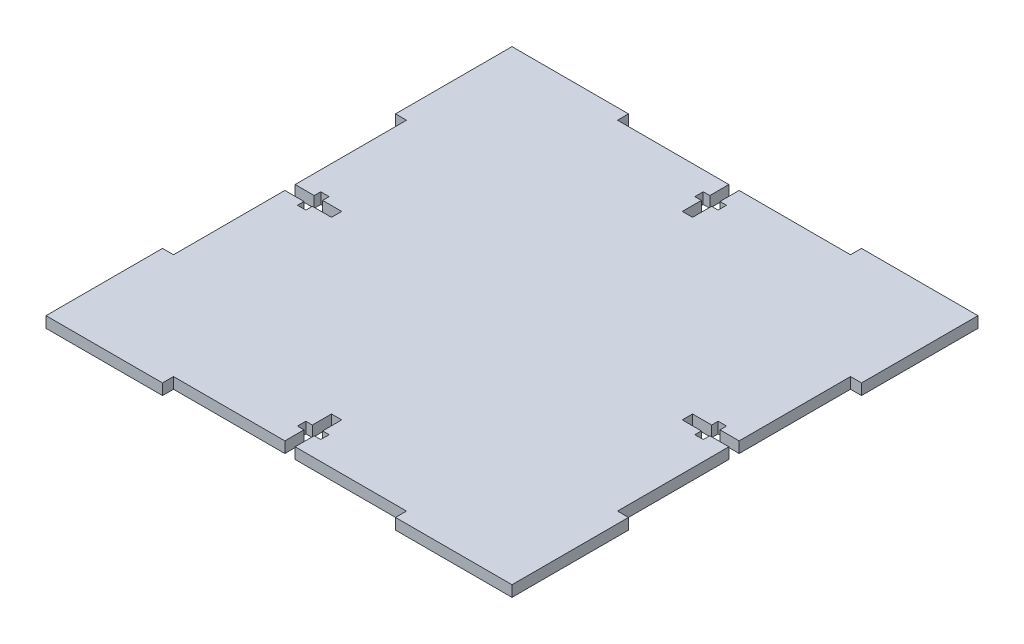
SolidWorks part; units mm, degrees
ref_plane "Front Plane" through (0, 0, 0) normal (0, 0, 1) x (1, 0, 0)
ref_plane "Top Plane" through (0, 0, 0) normal (0, 1, 0) x (1, 0, 0)
ref_plane "Right Plane" through (0, 0, 0) normal (1, 0, 0) x (0, 0, -1)
sketch "Sketch1" plane through (0, 0, 0) normal (0, 1, 0) x (1, 0, 0)
  line L1 (0, 0) -> (127, 0)
  line L2 (0, 0) -> (0, -127)
  line L3 (0, -127) -> (127, -127)
  line L4 (127, 0) -> (127, -127)
  dimension "D1" = 127
  dimension "D2" = 127
extrude "Boss-Extrude1" add sketch "Sketch1" along normal blind 2.9972
sketch "Sketch2" plane through (0, 2.9972, 0) normal (0, 1, 0) x (1, 0, 0)
  line L0 (0, -63.5) -> (127, -63.5) construction
  line L1 (31.75, -124.0028) -> (95.25, -124.0028)
  line L14 (95.25, -127) -> (95.25, -124.0028)
  line L23 (31.75, -127) -> (95.25, -127)
  line L36 (0, 0) -> (0, -127) construction
  line L37 (0, -31.75) -> (2.9972, -31.75)
  line L38 (0, -31.75) -> (0, -95.25)
  line L39 (0, -95.25) -> (2.9972, -95.25)
  line L40 (2.9972, -31.75) -> (2.9972, -95.25)
  line L41 (0, -127) -> (127, -127) construction
  line L42 (63.5, 0) -> (63.5, -127) construction
  line L43 (127, 0) -> (0, 0) construction
  line L45 (127, -95.25) -> (124.0028, -95.25)
  line L46 (127, -31.75) -> (124.0028, -31.75)
  line L47 (124.0028, -31.75) -> (124.0028, -95.25)
  line L48 (127, -31.75) -> (127, -95.25)
  line L49 (31.75, -127) -> (31.75, -124.0028)
  line L50 (31.75, 0) -> (95.25, 0)
  line L51 (31.75, 0) -> (31.75, -2.9972)
  line L52 (31.75, -2.9972) -> (95.25, -2.9972)
  line L53 (95.25, 0) -> (95.25, -2.9972)
  dimension "D1" = 63.5
  dimension "D2" = 31.75
  dimension "D3" = 2.9972
  dimension "D4" = 31.75
extrude "Cut-Extrude1" cut sketch "Sketch2" against normal blind 2.9972
sketch "Sketch3" plane through (0, 2.9972, 0) normal (0, 1, 0) x (1, 0, 0)
  line L0 (95.25, -124.0028) -> (31.75, -124.0028) construction
  line L7 (124.0028, -63.5) -> (1.4986, -63.5) construction
  line L8 (124.0028, -31.75) -> (124.0028, -95.25) construction
  line L13 (63.5, -2.9972) -> (63.5, -124.0028) construction
  line L14 (31.75, -2.9972) -> (95.25, -2.9972) construction
  line L18 (2.9972, -63.5) -> (15.6972, -63.5) construction
  line L20 (63.5, -124.0028) -> (63.5, -111.3028) construction
  line L21 (2.9972, -64.897) -> (8.2042, -64.897)
  line L22 (2.9972, -64.897) -> (2.9972, -62.103)
  line L23 (2.9972, -62.103) -> (8.2042, -62.103)
  line L24 (15.6972, -64.897) -> (15.6972, -62.103)
  line L25 (2.9972, -64.897) -> (15.6972, -62.103) construction
  line L26 (2.9972, -62.103) -> (15.6972, -64.897) construction
  line L27 (8.2042, -66.675) -> (10.4902, -66.675)
  line L28 (8.2042, -66.675) -> (8.2042, -64.897)
  line L29 (8.2042, -60.325) -> (10.4902, -60.325)
  line L30 (10.4902, -66.675) -> (10.4902, -64.897)
  line L31 (8.2042, -66.675) -> (10.4902, -60.325) construction
  line L32 (8.2042, -60.325) -> (10.4902, -66.675) construction
  line L34 (2.9972, -95.25) -> (2.9972, -31.75) construction
  line L35 (62.103, -124.0028) -> (64.897, -124.0028)
  line L36 (62.103, -124.0028) -> (62.103, -118.7958)
  line L37 (62.103, -111.3028) -> (64.897, -111.3028)
  line L38 (64.897, -124.0028) -> (64.897, -118.7958)
  line L39 (62.103, -124.0028) -> (64.897, -111.3028) construction
  line L40 (62.103, -111.3028) -> (64.897, -124.0028) construction
  line L41 (60.325, -118.7958) -> (62.103, -118.7958)
  line L42 (60.325, -118.7958) -> (60.325, -116.5098)
  line L43 (60.325, -116.5098) -> (62.103, -116.5098)
  line L44 (66.675, -118.7958) -> (66.675, -116.5098)
  line L45 (60.325, -118.7958) -> (66.675, -116.5098) construction
  line L46 (60.325, -116.5098) -> (66.675, -118.7958) construction
  line L48 (118.7958, -66.675) -> (118.7958, -64.897)
  line L50 (124.0028, -64.897) -> (118.7958, -64.897)
  line L55 (124.0028, -64.897) -> (124.0028, -62.103)
  line L56 (124.0028, -62.103) -> (118.7958, -62.103)
  line L61 (118.7958, -62.103) -> (118.7958, -60.325)
  line L62 (118.7958, -60.325) -> (116.5098, -60.325)
  line L67 (116.5098, -62.103) -> (116.5098, -60.325)
  line L68 (116.5098, -62.103) -> (111.3028, -62.103)
  line L73 (111.3028, -64.897) -> (111.3028, -62.103)
  line L74 (116.5098, -64.897) -> (111.3028, -64.897)
  line L76 (116.5098, -66.675) -> (116.5098, -64.897)
  line L78 (118.7958, -66.675) -> (116.5098, -66.675)
  line L80 (8.2042, -62.103) -> (8.2042, -60.325)
  line L85 (62.103, -2.9972) -> (62.103, -8.2042)
  line L86 (60.325, -8.2042) -> (62.103, -8.2042)
  line L91 (60.325, -8.2042) -> (60.325, -10.4902)
  line L92 (60.325, -10.4902) -> (62.103, -10.4902)
  line L97 (62.103, -10.4902) -> (62.103, -15.6972)
  line L98 (62.103, -15.6972) -> (64.897, -15.6972)
  line L103 (64.897, -10.4902) -> (64.897, -15.6972)
  line L104 (64.897, -10.4902) -> (66.675, -10.4902)
  line L109 (66.675, -8.2042) -> (66.675, -10.4902)
  line L110 (64.897, -8.2042) -> (66.675, -8.2042)
  line L115 (64.897, -2.9972) -> (64.897, -8.2042)
  line L116 (62.103, -2.9972) -> (64.897, -2.9972)
  line L117 (10.4902, -62.103) -> (15.6972, -62.103)
  line L118 (10.4902, -62.103) -> (10.4902, -60.325)
  line L119 (10.4902, -64.897) -> (15.6972, -64.897)
  line L120 (63.2485, -118.7958) -> (63.7515, -118.7958) construction
  line L121 (62.103, -116.5098) -> (62.103, -111.3028)
  line L122 (64.897, -116.5098) -> (66.675, -116.5098)
  line L123 (64.897, -116.5098) -> (64.897, -111.3028)
  line L124 (64.897, -118.7958) -> (66.675, -118.7958)
  line L164 (1.4986, -31.75) -> (1.4986, -63.5) construction
  point P3 (63.5, -124.0028)
  point P20 (0, 0)
  point P21 (0, 0)
  point P22 (9.3472, -63.5)
  point P27 (9.3472, -63.5)
  point P36 (63.5, -117.6528)
  point P41 (63.5, -117.6528)
  point P49 (2.9972, -63.5)
  point P64 (0, 0)
  dimension "D5" = 2.794
  dimension "D6" = 12.7
  dimension "D7" = 6.35
  dimension "D8" = 2.286
  dimension "D9" = 2.794
  dimension "D10" = 12.7
  dimension "D11" = 2.286
  dimension "D12" = 6.35
extrude "Cut-Extrude2" cut sketch "Sketch3" against normal up to next
equation "\"D4@Sketch2\"=\"D2@Sketch2\""
